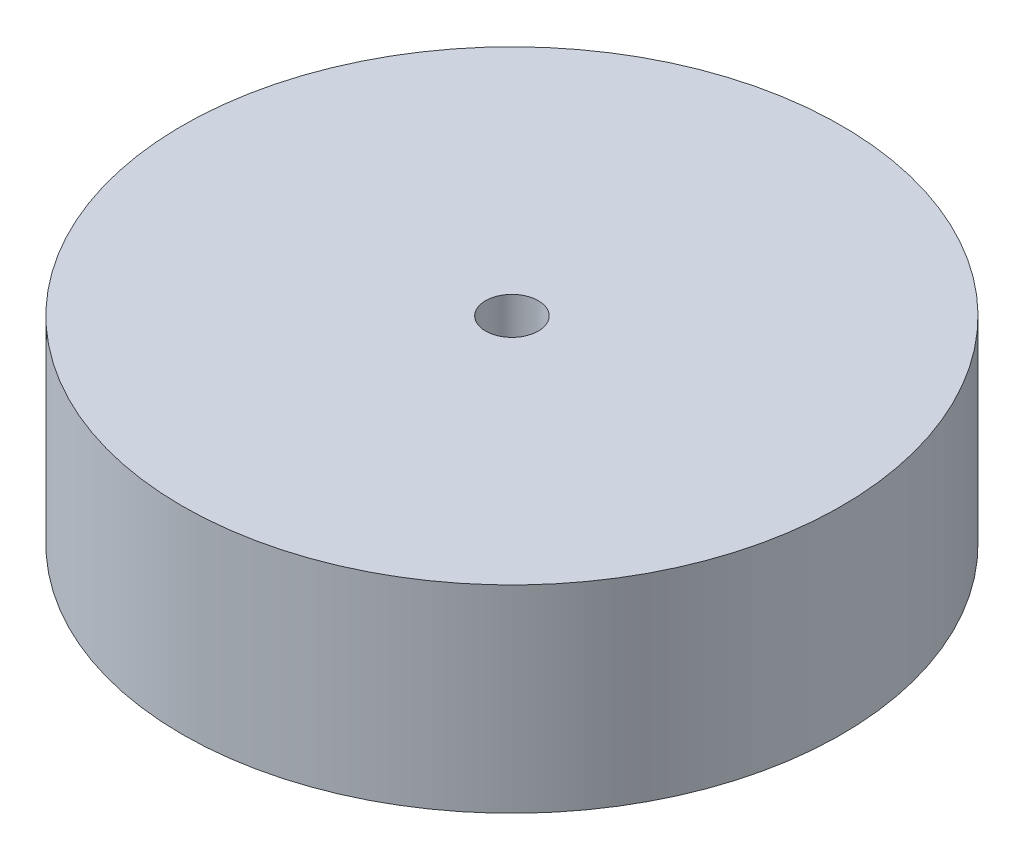
SolidWorks part; units mm, degrees
ref_plane "Front Plane" through (0, 0, 0) normal (0, 0, 1) x (1, 0, 0)
ref_plane "Top Plane" through (0, 0, 0) normal (0, 1, 0) x (1, 0, 0)
ref_plane "Right Plane" through (0, 0, 0) normal (1, 0, 0) x (0, 0, -1)
sketch "Sketch1" plane through (0, 0, 0) normal (0, 1, 0) x (1, 0, 0)
  circle A0 centre (0, 0) radius 50
  circle A1 centre (0, 0) radius 4
  dimension "D1" = 50
  dimension "D2" = 4
extrude "Boss-Extrude1" add sketch "Sketch1" along normal blind 30
